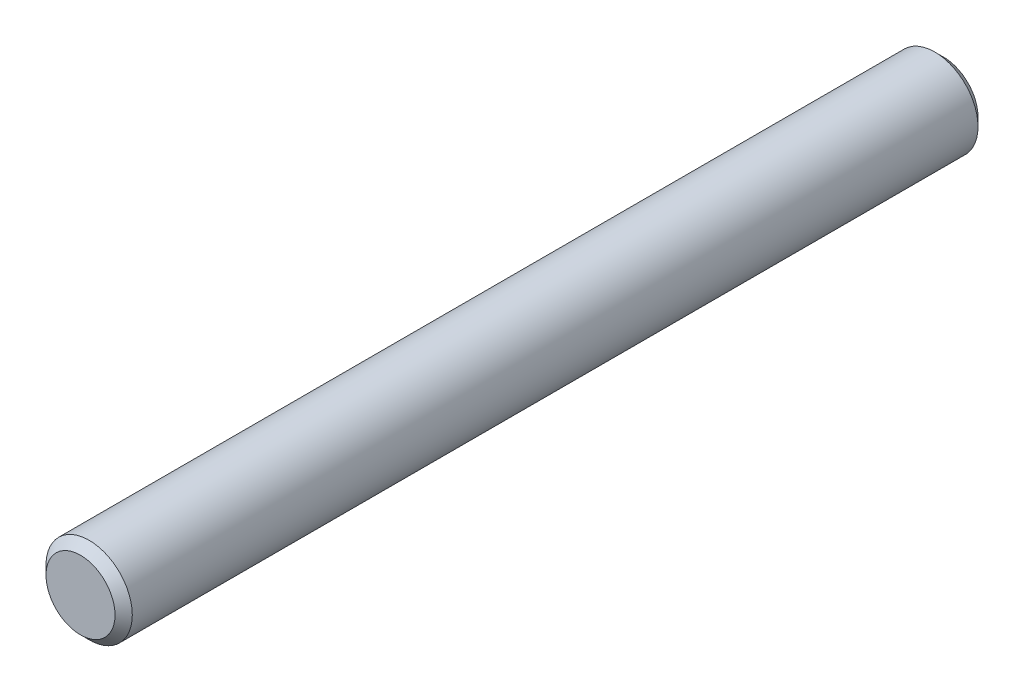
SolidWorks part; units mm, degrees
ref_plane "Front Plane" through (0, 0, 0) normal (0, 0, 1) x (1, 0, 0)
ref_plane "Top Plane" through (0, 0, 0) normal (0, 1, 0) x (1, 0, 0)
ref_plane "Right Plane" through (0, 0, 0) normal (1, 0, 0) x (0, 0, -1)
sketch "Sketch1" plane through (0, 0, 0) normal (0, 0, 1) x (1, 0, 0)
  circle A0 centre (0, 0) radius 5
  dimension "D1" = 10
extrude "Corpo Ø10×100" add sketch "Sketch1" along normal blind 100
chamfer "Chanfro 1×45°" distance 1 angle 45 2 edges at (5, 0, 0) (5, 0, 100)
